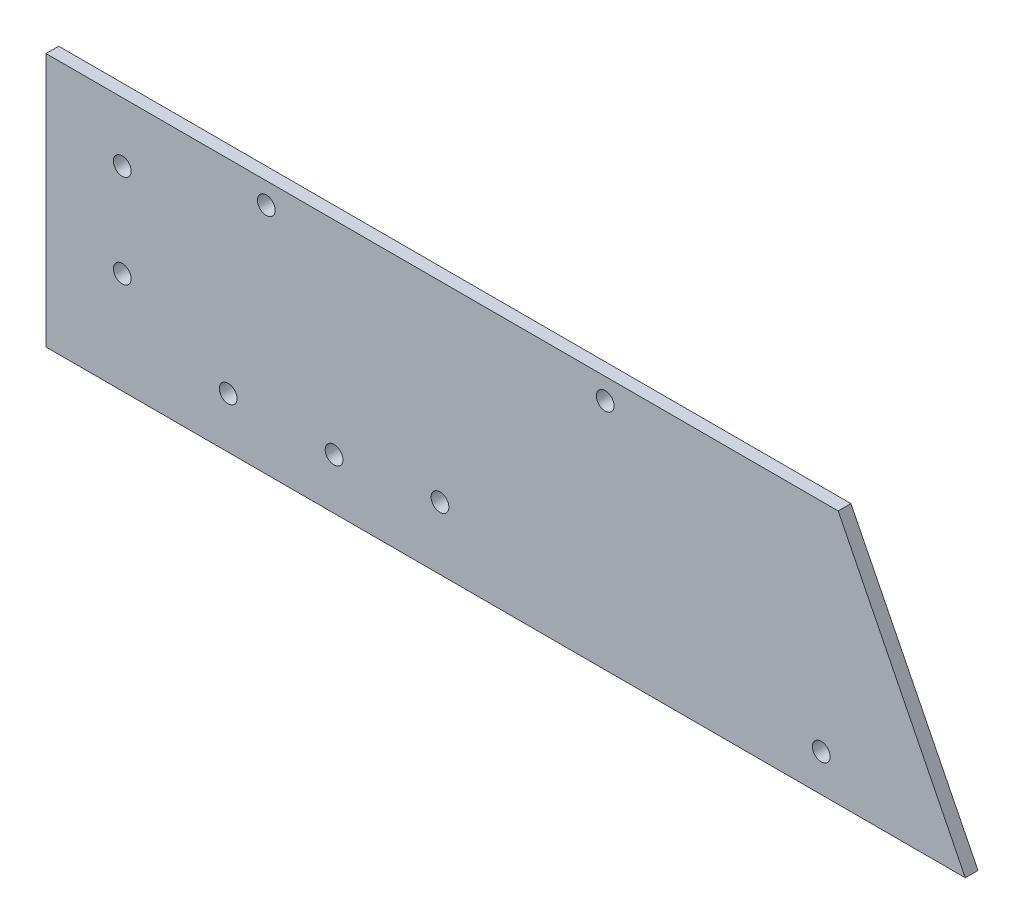
SolidWorks part; units mm, degrees
ref_plane "Płaszczyzna przednia" through (0, 0, 0) normal (0, 0, 1) x (1, 0, 0)
ref_plane "Płaszczyzna górna" through (0, 0, 0) normal (0, 1, 0) x (1, 0, 0)
ref_plane "Płaszczyzna prawa" through (0, 0, 0) normal (1, 0, 0) x (0, 0, -1)
sketch "Szkic1" plane through (0, 0, 0) normal (0, 0, 1) x (1, 0, 0)
  line L1 (0, 0) -> (217, 0)
  line L2 (0, 0) -> (0, 60)
  line L3 (0, 60) -> (217, 60)
  line L4 (217, 0) -> (217, 60)
  dimension "D1" = 217
  dimension "D2" = 60
extrude "Dodanie-wyciągnięcie1" add sketch "Szkic1" along normal blind 3
sketch "Szkic2" plane through (0, 0, 3) normal (0, 0, 1) x (1, 0, 0)
  line L0 (217, 0) -> (187, 60)
  line L1 (217, 60) -> (0, 60) construction
  line L2 (217, 0) -> (217, 60) construction
  line L3 (217, 0) -> (217, 60)
  line L4 (217, 60) -> (0, 60)
  line M3 (217, 0) -> (217, 60)
  line M4 (217, 60) -> (0, 60)
  dimension "D1" = 30
extrude "Wytnij-wyciągnięcie1" cut sketch "Szkic2" against normal through all contours L0 M3 M4
sketch "Szkic3" plane through (0, 0, 0) normal (0, 0, -1) x (-1, 0, 0)
  circle A0 centre (-68, 12) radius 2.1
  circle A1 centre (-43, 12) radius 2.1
  circle A2 centre (-18, 24) radius 2.1
extrude "Wytnij-wyciągnięcie2" cut sketch "Szkic3" against normal through all contours A2 | A1 | A0
sketch "Szkic4" plane through (0, 0, 3) normal (0, 0, 1) x (1, 0, 0)
  circle A0 centre (93, 14.8) radius 2.1
  circle A1 centre (183, 8.8) radius 2.1
extrude "Wytnij-wyciągnięcie3" cut sketch "Szkic4" against normal through all contours A0 | A1
sketch "Szkic5" plane through (0, 0, 3) normal (0, 0, 1) x (1, 0, 0)
  circle A0 centre (18, 46) radius 2.1
extrude "Wytnij-wyciągnięcie4" cut sketch "Szkic5" against normal through all
sketch "Szkic6" plane through (0, 0, 0) normal (0, 0, -1) x (-1, 0, 0)
  circle A2 centre (-52, 55) radius 2.1
  circle A3 centre (-132, 55) radius 2.1
extrude "Wytnij-wyciągnięcie5" cut sketch "Szkic6" against normal through all
